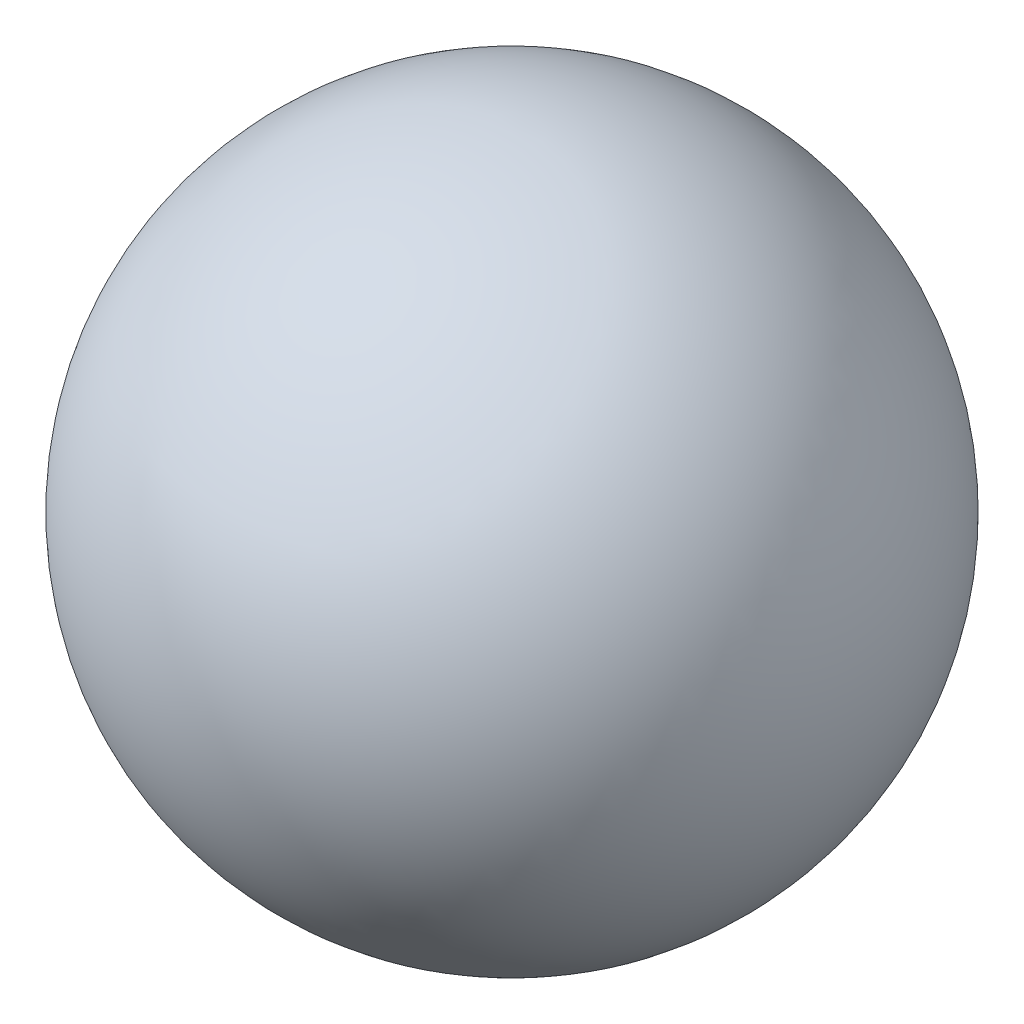
SolidWorks part; units mm, degrees
ref_plane "Front Plane" through (0, 0, 0) normal (0, 0, 1) x (1, 0, 0)
ref_plane "Top Plane" through (0, 0, 0) normal (0, 1, 0) x (1, 0, 0)
ref_plane "Right Plane" through (0, 0, 0) normal (1, 0, 0) x (0, 0, -1)
sketch "Sketch1" plane through (0, 0, 0) normal (1, 0, 0) x (0, 0, -1)
  line L0 (0, 11.15) -> (0, -11.15)
  arc A0 (0, -11.15) -> (0, 11.15) centre (0, 0) ccw
  point P4 (0, 0)
  dimension "D1" = 22.3
revolve "Revolve1" add sketch "Sketch1" angle 360 about L0
